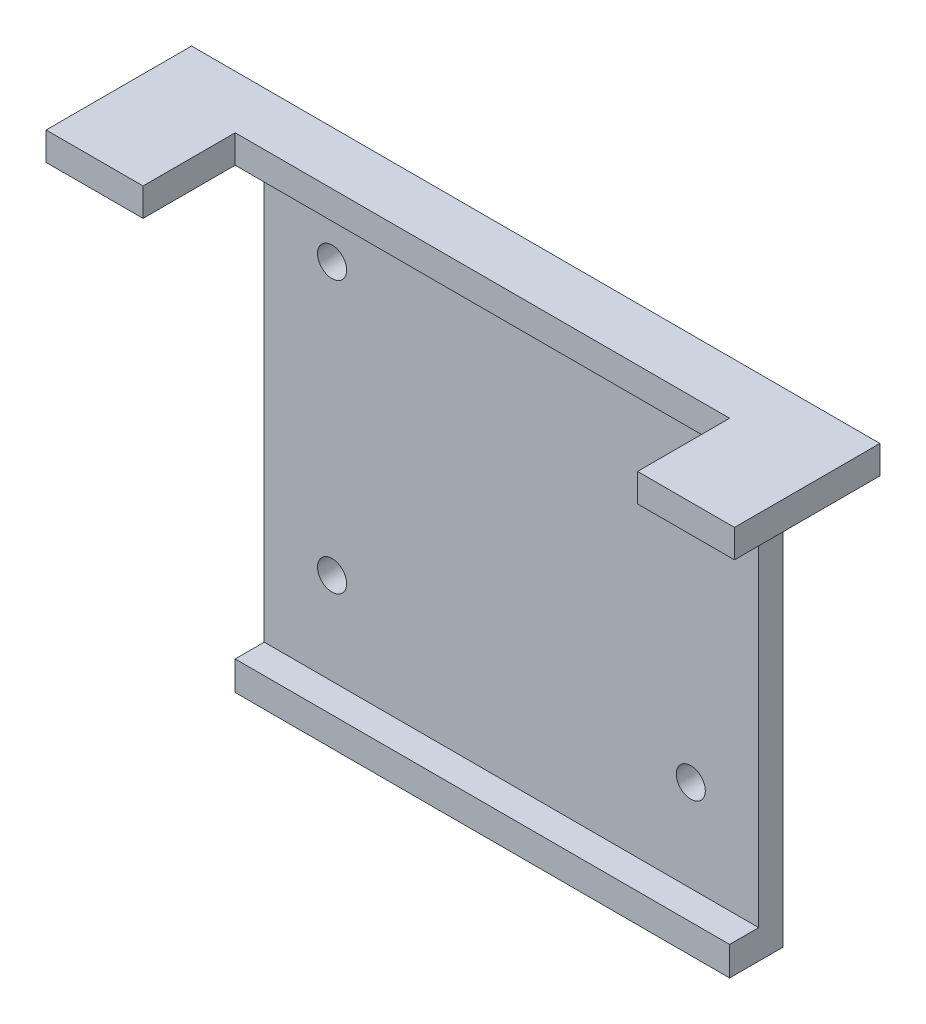
SolidWorks part; units mm, degrees
ref_plane "Plan de face" through (0, 0, 0) normal (0, 0, 1) x (1, 0, 0)
ref_plane "Plan de dessus" through (0, 0, 0) normal (0, 1, 0) x (1, 0, 0)
ref_plane "Plan de droite" through (0, 0, 0) normal (1, 0, 0) x (0, 0, -1)
sketch "Esquisse1" plane through (0, 0, 0) normal (0, 0, 1) x (1, 0, 0)
  line L1 (-25.5, 25) -> (25.5, 25)
  line L2 (-25.5, 25) -> (-25.5, -25)
  line L3 (-25.5, -25) -> (25.5, -25)
  line L4 (25.5, 25) -> (25.5, -25)
  line L5 (-25.5, 25) -> (25.5, -25) construction
  line L6 (-25.5, -25) -> (25.5, 25) construction
  point P0 (0, 0)
  dimension "D1" = 51
  dimension "D2" = 50
extrude "Boss.-Extru.1" add sketch "Esquisse1" along normal blind 2.5
sketch "Esquisse2" plane through (0, 0, 0) normal (0, 0, -1) x (-1, 0, 0)
  line L0 (-25.5, -25) -> (-25.5, 25) construction
  line L1 (-25.5, 25) -> (-35.5, 25)
  line L2 (-25.5, 25) -> (-25.5, 22.1)
  line L3 (-25.5, 22.1) -> (-35.5, 22.1)
  line L4 (-35.5, 25) -> (-35.5, 22.1)
  line L5 (-27, 22) -> (-39, 22) construction
  line L6 (0, -25) -> (0, -39.5081) construction
  line L7 (25.5, -25) -> (-25.5, -25) construction
  line L8 (25.5, 22.1) -> (35.5, 22.1)
  line L9 (35.5, 25) -> (35.5, 22.1)
  line L10 (25.5, 25) -> (35.5, 25)
  line L11 (25.5, 25) -> (25.5, 22.1)
  dimension "D1" = 10
  dimension "D2" = 0.1
extrude "Boss.-Extru.2" add sketch "Esquisse2" against normal blind 15
sketch "Esquisse3" plane through (0, 0, 2.5) normal (0, 0, 1) x (1, 0, 0)
  line L0 (25.5, -25) -> (25.5, 22.1) construction
  line L1 (-25.5, 25) -> (25.5, 25)
  line L2 (-25.5, 25) -> (-25.5, 22.1)
  line L3 (-25.5, 22.1) -> (25.5, 22.1)
  line L4 (25.5, 25) -> (25.5, 22.1)
  line L6 (-25.5, -25) -> (25.5, -25)
  line L7 (-25.5, -25) -> (-25.5, -22)
  line L8 (-25.5, -22) -> (25.5, -22)
  line L9 (25.5, -25) -> (25.5, -22)
  dimension "D1" = 3
extrude "Boss.-Extru.3" add sketch "Esquisse3" along normal blind 3
sketch "Esquisse4" plane through (0, 0, 0) normal (0, 0, -1) x (-1, 0, 0)
  line L0 (25.5, -25) -> (-25.5, -25) construction
  line L1 (25.5, 22.1) -> (25.5, -25) construction
  circle A0 centre (18.506, -12.5318) radius 1.5
  circle A1 centre (-18.494, -12.5318) radius 1.5
  circle A2 centre (-18.506, 15.4682) radius 1.5
  circle A3 centre (18.506, 15.4682) radius 1.5
  point P3 (0, 0)
  point P9 (-18.494, -12.5478)
  point P11 (-18.5061, 15.4522)
  point P13 (18.5059, 15.4682)
  point P15 (0, 0)
  point P20 (0, 0)
  point P21 (0, 0)
  point P22 (0, 0)
  point P23 (0, 0)
  dimension "D1" = 3
  dimension "D2" = 12.4682
  dimension "D3" = 6.994
  dimension "D4" = 28
  dimension "D5" = 37.012
  dimension "D6" = 28
  dimension "D7" = 37
extrude "Enlèv. mat.-Extru.1" cut sketch "Esquisse4" against normal through all
